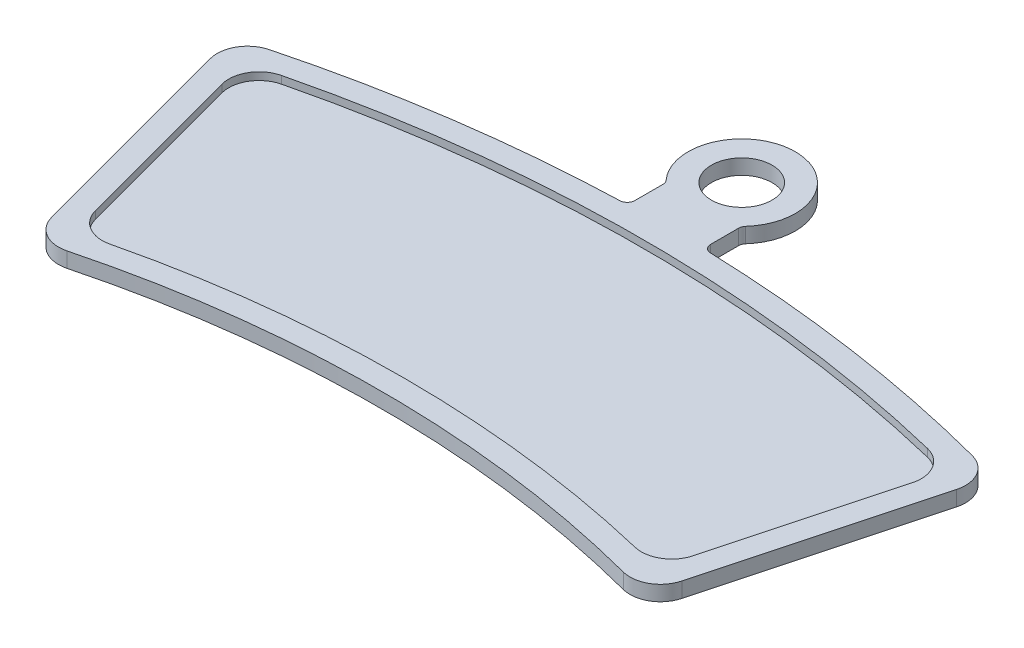
SolidWorks part; units mm, degrees
material "Plain Carbon Steel"
ref_plane "Front Plane" through (0, 0, 0) normal (0, 0, 1) x (1, 0, 0)
ref_plane "Top Plane" through (0, 0, 0) normal (0, 1, 0) x (1, 0, 0)
ref_plane "Right Plane" through (0, 0, 0) normal (1, 0, 0) x (0, 0, -1)
sketch "Sketch1" plane through (0, 0, 0) normal (0, 1, 0) x (1, 0, 0)
  line L0 (0, 0) -> (0, 99.9694) construction
  line L1 (-23.2937, 86.9333) -> (-19.2044, 71.6717) construction
  line L2 (23.2937, 86.9333) -> (19.2044, 71.6717) construction
  line L3 (-25.1276, 87.9821) -> (-20.261, 69.8196)
  line L4 (25.1276, 87.9821) -> (20.261, 69.8196)
  line L5 (2.4998, 91.4658) -> (2.4998, 94)
  line L6 (-2.5, 91.4658) -> (-2.5, 94.0002)
  circle A0 centre (0, 0) radius 90 construction
  circle A1 centre (0, 0) radius 74.2 construction
  arc A2 (23.2937, 86.9333) -> (-23.2937, 86.9333) centre (0, 0) ccw construction
  arc A3 (19.2044, 71.6717) -> (-19.2044, 71.6717) centre (0, 0) ccw construction
  arc A4 (25.1276, 87.9821) -> (2.4998, 91.4658) centre (0, 0) ccw
  arc A5 (20.261, 69.8196) -> (-20.261, 69.8196) centre (0, 0) ccw
  arc A6 (2.4998, 94) -> (-2.5, 94.0002) centre (0, 96.5) ccw
  arc A7 (-2.5, 91.4658) -> (-25.1276, 87.9821) centre (0, 0) ccw
  arc A8 (25.1276, 87.9821) -> (-25.1276, 87.9821) centre (0, 0) ccw construction
  circle A9 centre (0, 0) radius 91.5 construction
  point P7 (0, 74.2)
  point P18 (0, 91.5)
  point P26 (0, 96.5)
  dimension "D1" = 180
  dimension "D2" = 148.4
  dimension "D5" = 2.5
  dimension "D3" = 15
  dimension "D6" = 2.5
  dimension "D7" = 2.5
  dimension "D8" = 5
  dimension "D4" = 1.5
extrude "Boss-Extrude1" add sketch "Sketch1" along normal blind 1
sketch "Sketch2" plane through (0, 1, 0) normal (0, 1, 0) x (1, 0, 0)
  line L0 (19.2044, 71.6717) -> (23.2937, 86.9333)
  line L1 (-23.2937, 86.9333) -> (-19.2044, 71.6717)
  arc A0 (-23.2937, 86.9333) -> (23.2937, 86.9333) centre (0, 0) cw
  arc A1 (-19.2044, 71.6717) -> (19.2044, 71.6717) centre (0, 0) cw
  circle A2 centre (0, 0) radius 90 construction
  point P10 (0, 90)
  point P13 (0, 74.2)
extrude "Cut-Extrude2" cut sketch "Sketch2" against normal blind 0.5
fillet "Fillet2" radius 2 8 edges at (-25.1276, 0.5, -87.9821) (-20.261, 0.5, -69.8196) (20.261, 0.5, -69.8196) (25.1276, 0.5, -87.9821) (-19.2044, 0.75, -71.6717) (19.2044, 0.75, -71.6717) (23.2937, 0.75, -86.9333) (-23.2937, 0.75, -86.9333)
fillet "Fillet3" radius 0.5 4 edges at (2.4998, 0.5, -94) (-2.5, 0.5, -94.0002) (-2.5, 0.5, -91.4658) (2.4998, 0.5, -91.4658)
sketch "Sketch3" plane through (0, 1, 0) normal (0, 1, 0) x (1, 0, 0)
  point P0 (0, 96.5)
hole_wizard "Ø4.0mm Dowel Hole1" positions "Sketch3" profile "Sketch4" hole size "Ø4.0" standard "ANSI Metric" end condition through all
sketch "Sketch4" plane through (0, 1, -96.5) normal (1, 0, 0) x (0, 0, 1)
  line L0 (0, 0) -> (0, 1)
  line L1 (0, 1) -> (2, 1)
  line L2 (2, 1) -> (2, 0)
  line L5 (2, 0) -> (0, 0)
  line L11 (0, -6.35) -> (0, 107.95) construction
  dimension "Thru Hole Dia." = 4
  dimension "Thru Hole Depth" = 1
